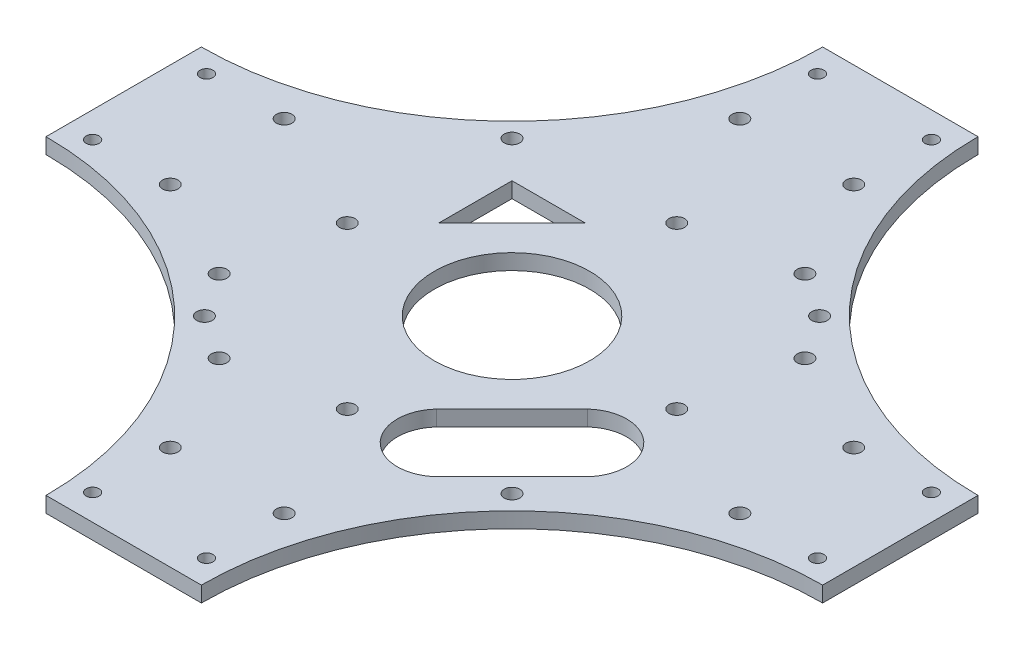
SolidWorks part; units mm, degrees
ref_plane "前视基准面" through (0, 0, 0) normal (0, 0, 1) x (1, 0, 0)
ref_plane "上视基准面" through (0, 0, 0) normal (0, 1, 0) x (1, 0, 0)
ref_plane "右视基准面" through (0, 0, 0) normal (1, 0, 0) x (0, 0, -1)
sketch "草图1" plane through (0, 0, 0) normal (0, 1, 0) x (1, 0, 0)
  line L0 (0, 0) -> (0, 75)
  line L1 (0, 0) -> (75, 0)
  line L2 (0, 0) -> (0, -75)
  line L3 (0, 0) -> (-75, 0)
  line L4 (0, 75) -> (15, 75)
  line L5 (0, 75) -> (-15, 75)
  line L6 (75, 0) -> (75, 15)
  line L7 (75, 0) -> (75, -15)
  line L8 (0, -75) -> (15, -75)
  line L9 (0, -75) -> (-15, -75)
  line L10 (-75, 0) -> (-75, -15)
  line L11 (-75, 0) -> (-75, 15)
  line L12 (75, 0) -> (70, 0)
  arc A0 (-75, 15) -> (-15, 75) centre (-75, 75) ccw
  arc A1 (15, 75) -> (75, 15) centre (75, 75) ccw
  arc A2 (75, -15) -> (15, -75) centre (75, -75) ccw
  arc A3 (-15, -75) -> (-75, -15) centre (-75, -75) ccw
  circle A4 centre (-11, 70) radius 1.25
  circle A5 centre (11, 70) radius 1.25
  circle A6 centre (70, -11) radius 1.25
  circle A7 centre (70, 11) radius 1.25
  circle A8 centre (-11, -70) radius 1.25
  circle A9 centre (11, -70) radius 1.25
  circle A10 centre (-70, 11) radius 1.25
  circle A11 centre (-70, -11) radius 1.25
  point P9 (0, 0)
  point P21 (0, 0)
  point P32 (0, 0)
  point P35 (0, 0)
  point P44 (0, 0)
  dimension "D1" = 4
extrude "凸台-拉伸1" add sketch "草图1" along normal blind 3 contours A2 L7 L1 L2 L8 A9 A6 | A3 L9 L2 L3 L10 A11 A8 | A0 L11 L3 L0 L5 A4 A10 | A1 L4 L0 L1 L6 A7 A5
sketch "草图2" plane through (0, 0, 0) normal (0, -1, 0) x (1, 0, 0)
  line L0 (0, 0) -> (-32.5736, -32.5736)
  line L1 (0, 0) -> (32.5736, -32.5736)
  line L2 (-31.4663, 0.3536) -> (-0.3536, 31.4663)
  line L3 (31.4663, -0.3536) -> (-0.3536, 31.4663)
  line L4 (0.3536, -31.4663) -> (31.4663, -0.3536)
  line L5 (0.3536, -31.4663) -> (-31.4663, 0.3536)
  arc A0 (-15, -75) -> (-75, -15) centre (-75, -75) ccw construction
  circle A2 centre (0.3536, -31.4663) radius 1.5
  circle A3 centre (31.4663, -0.3536) radius 1.5
  circle A4 centre (-0.3536, 31.4663) radius 1.5
  circle A5 centre (-31.4663, 0.3536) radius 1.5
  point P12 (-15.5563, -15.5563)
  point P16 (-15.9099, 15.9099)
  point P17 (15.9099, -15.9099)
extrude "切除-拉伸1" cut sketch "草图2" against normal blind 3 contours A3 | A2 | A5 | A4
sketch "草图3" plane through (0, 3, 0) normal (0, 1, 0) x (1, 0, 0)
  line L0 (0.3536, 31.4663) -> (-31.4663, -0.3536)
  line L1 (-15.5563, 15.5563) -> (-22.6274, 22.6274)
  line L2 (-15.5563, 15.5563) -> (-12.0208, 19.0919)
  line L3 (-15.5563, 15.5563) -> (-19.0919, 12.0208)
  line L4 (-19.0919, 12.0208) -> (-22.6274, 22.6274)
  line L5 (-12.0208, 19.0919) -> (-22.6274, 22.6274)
extrude "切除-拉伸2" cut sketch "草图3" against normal blind 3 contours L0 L5 L1 | L4 L0 L1
sketch "草图4" plane through (0, 3, 0) normal (0, 1, 0) x (1, 0, 0)
  line L0 (31.4663, 0.3536) -> (-0.3536, -31.4663)
  line L1 (0, 0) -> (21.2132, -21.2132)
  line L2 (28.2843, -14.1421) -> (14.1421, -28.2843)
  line L3 (14.1421, -28.2843) -> (28.2843, -14.1421) construction
  line L4 (8.4817, -22.6239) -> (22.6239, -8.4817)
  line L5 (19.8025, -33.9447) -> (33.9447, -19.8025)
  arc A0 (8.4817, -22.6239) -> (19.8025, -33.9447) centre (14.1421, -28.2843) ccw
  arc A1 (33.9447, -19.8025) -> (22.6239, -8.4817) centre (28.2843, -14.1421) ccw
  point P9 (21.2132, -21.2132)
extrude "切除-拉伸3" cut sketch "草图4" against normal blind 3
sketch "草图5" plane through (0, 3, 0) normal (0, 1, 0) x (1, 0, 0)
  line L0 (-12.0208, 19.0919) -> (-8.4853, 22.6274)
  line L1 (-8.4853, 22.6274) -> (-22.6274, 22.6274)
  line L2 (-19.0919, 12.0208) -> (-22.6274, 8.4853)
  line L3 (-22.6274, 8.4853) -> (-22.6274, 22.6274)
  line L4 (-12.0208, 19.0919) -> (-22.6274, 22.6274)
  line M28 (-19.0919, 12.0208) -> (-22.6274, 22.6274)
extrude "切除-拉伸4" cut sketch "草图5" against normal blind 10 contours L3 L2 M28 | L4 L0 L1
sketch "草图6" plane through (0, 3, 0) normal (0, 1, 0) x (1, 0, 0)
  line L0 (0, 0) -> (-28.2843, -28.2843)
  line L1 (-28.2843, -28.2843) -> (-35.3553, -21.2132)
  line L2 (0, 0) -> (-22.6274, 22.6274)
  circle A0 centre (-35.3553, -21.2132) radius 1.5
  circle A1 centre (-21.2132, -35.3553) radius 1.5
  circle A2 centre (35.3553, 21.2132) radius 1.5
  circle A3 centre (21.2132, 35.3553) radius 1.5
extrude "切除-拉伸5" cut sketch "草图6" against normal blind 10 contours A1 | A0 | A2 | A3
sketch "草图7" plane through (0, 3, 0) normal (0, 1, 0) x (1, 0, 0)
  circle A0 centre (-29.6985, 29.6985) radius 1.5
  circle A1 centre (29.6985, 29.6985) radius 1.5
  circle A2 centre (29.6985, -29.6985) radius 1.5
  circle A3 centre (-29.6985, -29.6985) radius 1.5
  point P11 (0, 0)
  dimension "D1" = 4
extrude "切除-拉伸8" cut sketch "草图7" against normal blind 10
sketch "草图8" plane through (0, 3, 0) normal (0, 1, 0) x (1, 0, 0)
  circle A0 centre (-11, 55) radius 1.5
  circle A1 centre (11, 55) radius 1.5
  circle A2 centre (55, 11) radius 1.5
  circle A3 centre (55, -11) radius 1.5
  circle A4 centre (11, -55) radius 1.5
  circle A5 centre (-11, -55) radius 1.5
  circle A6 centre (-55, -11) radius 1.5
  circle A7 centre (-55, 11) radius 1.5
  point P21 (0, 0)
  dimension "D1" = 4
extrude "切除-拉伸9" cut sketch "草图8" against normal blind 10
sketch "草图9" plane through (0, 3, 0) normal (0, 1, 0) x (1, 0, 0)
  circle A0 centre (0, 0) radius 15
extrude "切除-拉伸10" cut sketch "草图9" against normal blind 10
